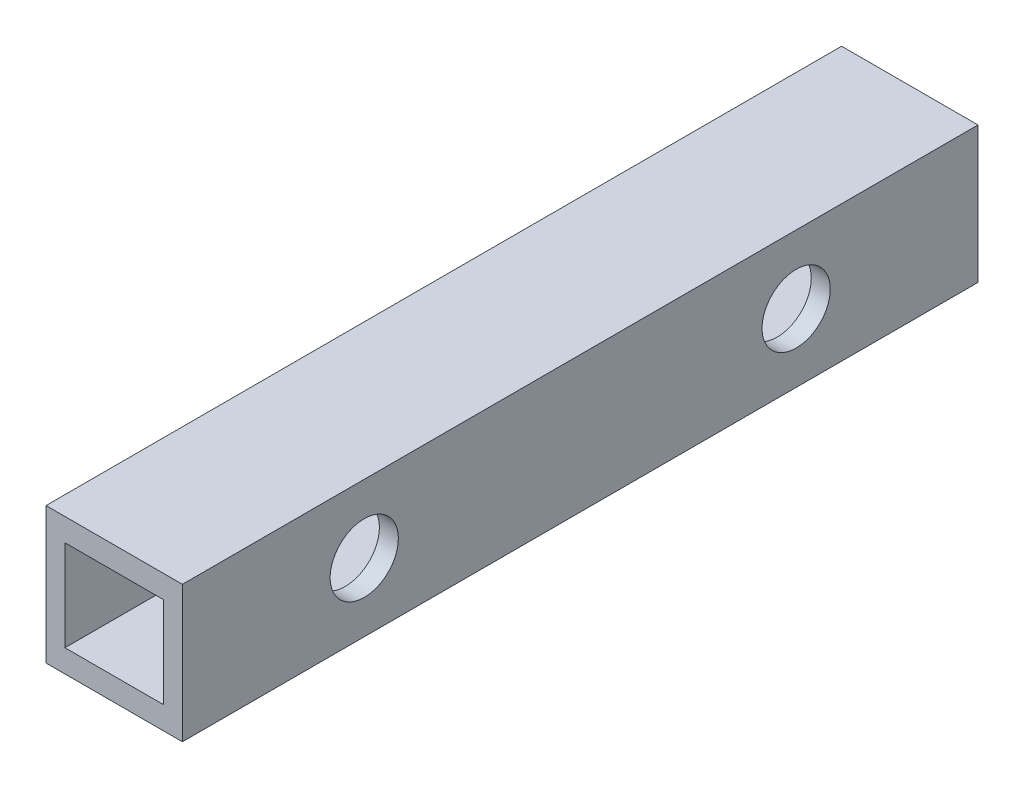
SolidWorks part; units mm, degrees
ref_plane "Front Plane" through (0, 0, 0) normal (0, 0, 1) x (1, 0, 0)
ref_plane "Top Plane" through (0, 0, 0) normal (0, 1, 0) x (1, 0, 0)
ref_plane "Right Plane" through (0, 0, 0) normal (1, 0, 0) x (0, 0, -1)
sketch "Sketch1" plane through (0, 0, 0) normal (0, 0, 1) x (1, 0, 0)
  line L1 (-30, -30) -> (30, -30)
  line L2 (-30, -30) -> (-30, 30)
  line L3 (-30, 30) -> (30, 30)
  line L4 (30, -30) -> (30, 30)
  line L5 (-30, -30) -> (30, 30) construction
  line L6 (-30, 30) -> (30, -30) construction
  point P0 (0, 0)
  dimension "D1" = 60
  dimension "D2" = 60
extrude "Boss-Extrude1" add sketch "Sketch1" along normal blind 350
sketch "Sketch2" plane through (0, 0, 0) normal (0, 0, -1) x (-1, 0, 0)
  line L1 (-21.6562, -20) -> (21.6562, -20)
  line L2 (-21.6562, -20) -> (-21.6562, 20)
  line L3 (-21.6562, 20) -> (21.6562, 20)
  line L4 (-30, 30) -> (-30, -30)
  line L5 (-30, -30) -> (30, -30)
  line L6 (30, -30) -> (30, 30)
  line L7 (30, 30) -> (-30, 30)
  line L8 (-30, 30) -> (-30, -30)
  line L9 (-30, -30) -> (30, -30)
  line L10 (30, -30) -> (30, 30)
  line L11 (30, 30) -> (-30, 30)
  line L12 (21.6562, -20) -> (21.6562, 20)
  line L13 (-21.6562, -20) -> (21.6562, 20) construction
  line L14 (-21.6562, 20) -> (21.6562, -20) construction
  point P2 (0, 0)
  dimension "D2" = 10
  dimension "D3" = 40
  dimension "D1" = 0
sketch "Sketch3" plane through (0, 0, 0) normal (0, 0, -1) x (-1, 0, 0)
  line L1 (-21.6562, -20) -> (21.6562, -20)
  line L2 (-21.6562, -20) -> (-21.6562, 20)
  line L3 (-21.6562, 20) -> (21.6562, 20)
  line L4 (21.6562, -20) -> (21.6562, 20)
  line L5 (-21.6562, -20) -> (21.6562, 20) construction
  line L6 (-21.6562, 20) -> (21.6562, -20) construction
  point P0 (0, 0)
extrude "Cut-Extrude2" cut sketch "Sketch3" against normal blind 375
sketch "Sketch4" plane through (30, 0, 0) normal (1, 0, 0) x (0, 0, -1)
  line L0 (-350, 30) -> (0, 30) construction
  line L1 (0, -30) -> (0, 30) construction
  circle A0 centre (-80, 0) radius 15
  dimension "D1" = 30
  dimension "D2" = 30
  dimension "D3" = 80
extrude "Cut-Extrude3" cut sketch "Sketch4" against normal blind 375
ref_plane "Plane1" through (0, 0, 175) normal (0, 0, -1) x (-1, 0, 0)
mirror "Mirror1" about plane through (0, 0, 175) normal (0, 0, -1) of "Cut-Extrude3"
